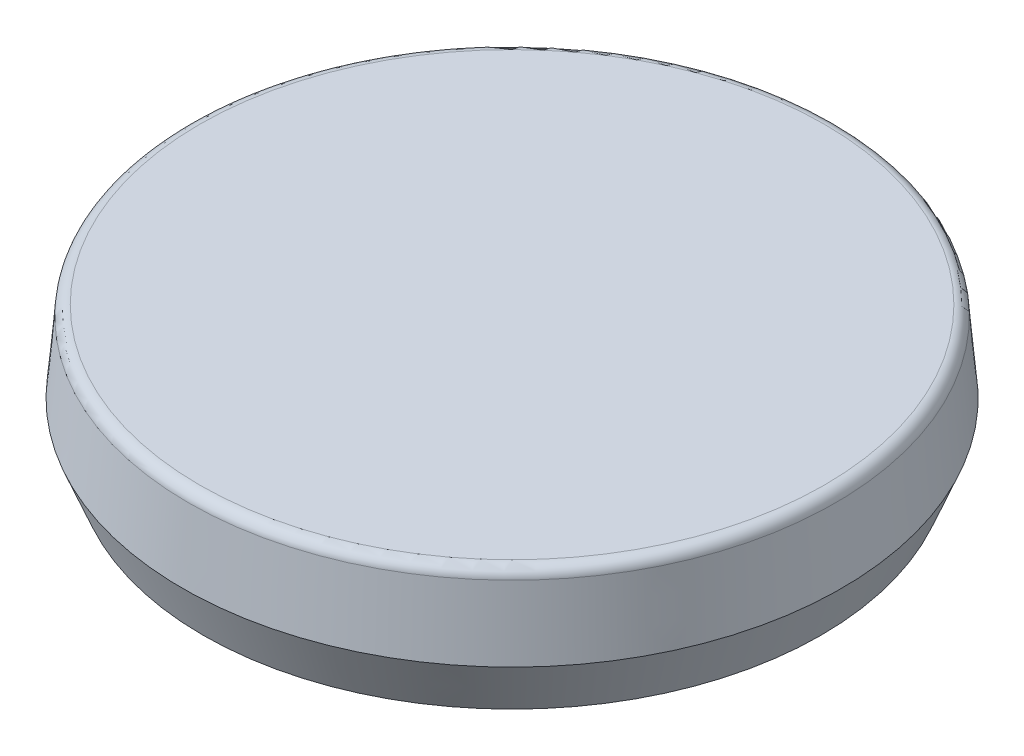
SolidWorks part; units mm, degrees
material "ABS"
ref_plane "Front Plane" through (0, 0, 0) normal (0, 0, 1) x (1, 0, 0)
ref_plane "Top Plane" through (0, 0, 0) normal (0, 1, 0) x (1, 0, 0)
ref_plane "Right Plane" through (0, 0, 0) normal (1, 0, 0) x (0, 0, -1)
sketch "Sketch1" plane through (0, 0, 0) normal (0, 0, 1) x (1, 0, 0)
  line L0 (0, 0) -> (0, 1.2)
  line L1 (0, 0) -> (2.8127, 0)
  line L2 (2.8127, 0) -> (3, 0.4636)
  line L3 (3, 0.4636) -> (2.9356, 1.2)
  line L4 (2.9356, 1.2) -> (0, 1.2)
  dimension "D1" = 1.2
  dimension "D2" = 112
  dimension "D3" = 153
  dimension "D4" = 3
  dimension "D5" = 0.5
revolve "Revolve1" add sketch "Sketch1" angle 360 about L0
fillet "Fillet1" radius 0.1 1 edges at (0, 1.2, -2.9356)
sketch "Sketch2" plane through (0, 0, 0) normal (0, -1, 0) x (1, 0, 0)
  circle A0 centre (0, 0) radius 2.5
  dimension "D1" = 5
extrude "Cut-Extrude1" cut sketch "Sketch2" against normal blind 0.5
